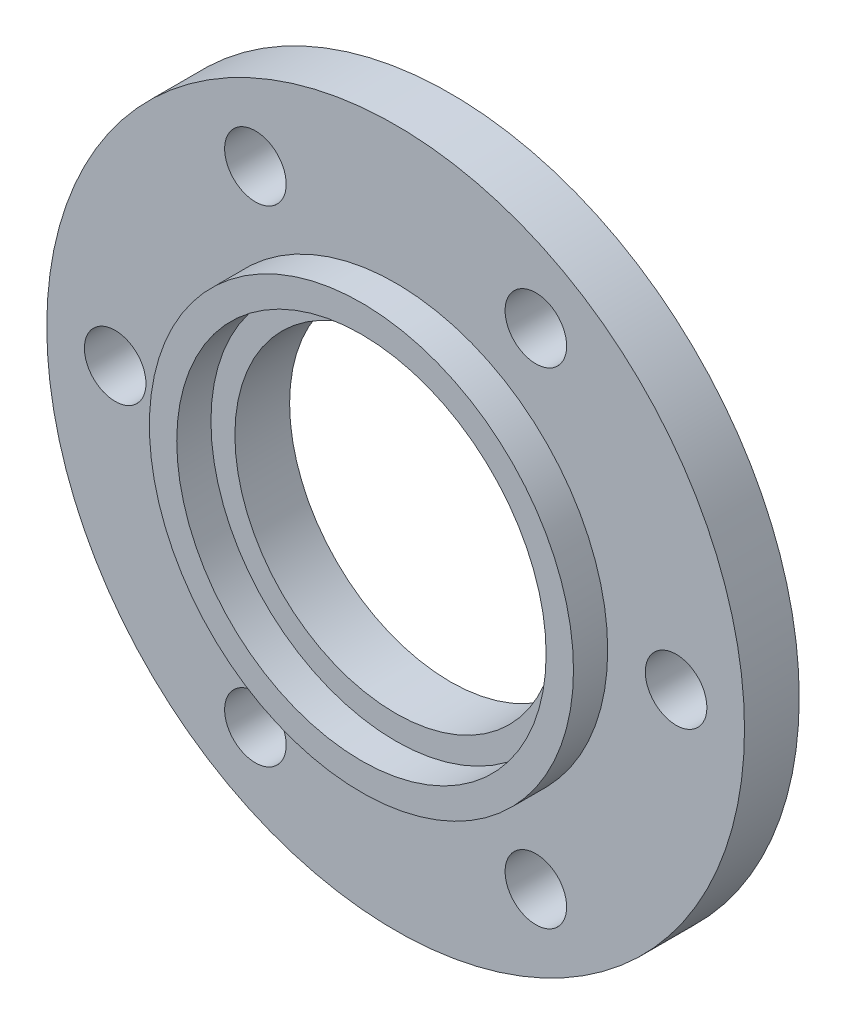
SolidWorks part; units mm, degrees
ref_plane "前视基准面" through (0, 0, 0) normal (0, 0, 1) x (1, 0, 0)
ref_plane "上视基准面" through (0, 0, 0) normal (0, 1, 0) x (1, 0, 0)
ref_plane "右视基准面" through (0, 0, 0) normal (1, 0, 0) x (0, 0, -1)
other "Configuration Table"
sketch "草图1" plane through (0, 0, 0) normal (0, 0, 1) x (1, 0, 0)
  circle A0 centre (0, 0) radius 51
  circle A1 centre (0, 0) radius 23.5
  dimension "D1" = 102
  dimension "D2" = 47
extrude "凸台-拉伸1" add sketch "草图1" along normal blind 8
sketch "草图2" plane through (0, 0, 8) normal (0, 0, 1) x (1, 0, 0)
  circle A0 centre (0, 0) radius 27
  circle A1 centre (0, 0) radius 31
  dimension "D1" = 54
  dimension "D2" = 62
extrude "凸台-拉伸2" add sketch "草图2" along normal blind 5
sketch "草图3" plane through (0, 0, 8) normal (0, 0, 1) x (1, 0, 0)
  circle A0 centre (0, 0) radius 41 construction
  circle A1 centre (41, 0) radius 4.5
  circle A2 centre (20.5, -35.507) radius 4.5
  circle A3 centre (-20.5, -35.507) radius 4.5
  circle A4 centre (-41, 0) radius 4.5
  circle A5 centre (-20.5, 35.507) radius 4.5
  circle A6 centre (20.5, 35.507) radius 4.5
  circle A7 centre (0, 0) radius 31 construction
  point P5 (41, 0)
  point P19 (0, 0)
  dimension "D1" = 9
  dimension "D2" = 6
extrude "切除-拉伸1" cut sketch "草图3" against normal up to next
